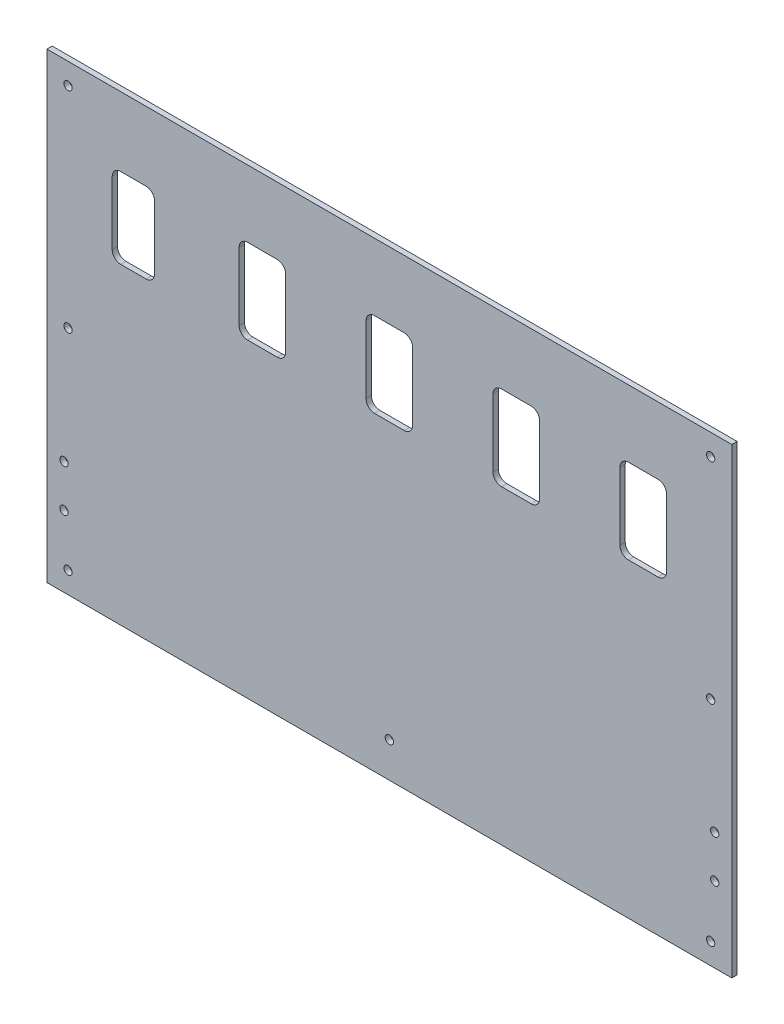
SolidWorks part; units mm, degrees
material "ABS PC"
ref_plane "Front Plane" through (0, 0, 0) normal (0, 0, 1) x (1, 0, 0)
ref_plane "Top Plane" through (0, 0, 0) normal (0, 1, 0) x (1, 0, 0)
ref_plane "Right Plane" through (0, 0, 0) normal (1, 0, 0) x (0, 0, -1)
sketch "Sketch1" plane through (0, 0, 0) normal (0, 0, 1) x (1, 0, 0)
  line L1 (-205.5812, -138.684) -> (205.5812, -138.684)
  line L2 (-205.5812, -138.684) -> (-205.5812, 138.684)
  line L3 (-205.5812, 138.684) -> (205.5812, 138.684)
  line L4 (205.5812, -138.684) -> (205.5812, 138.684)
  line L5 (0, 138.684) -> (0, -138.684) construction
  line L6 (-205.5812, 0) -> (205.5813, 0) construction
  point P0 (0, 0)
  point P4 (-137.0013, 0)
  point P5 (137.0013, 0)
  point P6 (0, 97.0788)
  point P7 (0, -97.0788)
  dimension "Width" = 277.368
  dimension "Break" = 68.58
  dimension "D2" = 68.58
  dimension "D1" = 41.6052
  dimension "D3" = 41.6052
  dimension "D4" = 411.1625
sketch "Sketch2" plane through (0, 0, 0) normal (1, 0, 0) x (0, 0, -1)
  line L0 (-1.5875, -138.684) -> (1.5875, -138.684)
  dimension "Thickness" = 3.175
sketch "Sketch3" plane through (0, 0, 0) normal (0, 0, 1) x (1, 0, 0)
  line L0 (-205.5812, -138.684) -> (-205.5812, 138.684) construction
  line L1 (-205.5812, -138.684) -> (205.5812, -138.684) construction
  line L2 (205.5812, -138.684) -> (205.5812, 138.684) construction
  line L3 (-205.5812, 138.684) -> (205.5812, 138.684) construction
  line L4 (-205.5812, -138.684) -> (-205.5812, 138.684)
  line L5 (-205.5812, -138.684) -> (205.5812, -138.684)
  line L6 (205.5812, -138.684) -> (205.5812, 138.684)
  line L7 (-205.5812, 138.684) -> (205.5812, 138.684)
extrude "Boss-Extrude1" add sketch "Sketch3" along normal mid plane 3.175
sketch "Sketch4" plane through (0, 0, 1.5875) normal (0, 0, 1) x (1, 0, 0)
  line L0 (-227.6475, 73.0327) -> (-161.29, 73.0327) construction
  line L1 (-82.55, 73.0327) -> (-82.55, 98.4327) construction
  line L2 (-82.55, 98.4327) -> (-90.17, 98.4327) construction
  line L3 (-161.29, 73.0327) -> (-161.29, 97.1627) construction
  line L6 (-227.6475, -105.791) -> (-227.6475, 52.959) construction
  line L7 (-227.6475, -115.316) -> (-227.6475, 138.684) construction
  line L8 (-161.29, 73.0327) -> (-82.55, 73.0327) construction
  line L9 (-82.55, 73.0327) -> (-6.35, 73.0327) construction
  line L10 (-6.35, 73.0327) -> (69.85, 73.0327) construction
  line L11 (69.85, 73.0327) -> (146.05, 73.0327) construction
  line L12 (-82.55, 73.0327) -> (-82.55, 47.6327) construction
  line L13 (-82.55, 47.6327) -> (-62.23, 47.6327) construction
  line L16 (-161.29, 97.1627) -> (-166.37, 97.1627) construction
  line L17 (-161.29, 73.0327) -> (-161.29, 48.9027) construction
  line L18 (-161.29, 48.9027) -> (-140.97, 48.9027) construction
  line L19 (-6.35, 73.0327) -> (-6.35, 98.4327) construction
  line L24 (-6.35, 98.4327) -> (-13.97, 98.4327) construction
  line L25 (-6.35, 73.0327) -> (-6.35, 47.6327) construction
  line L26 (-6.35, 47.6327) -> (13.97, 47.6327) construction
  line L27 (69.85, 73.0327) -> (69.85, 98.4327) construction
  line L28 (-8.89, 98.4327) -> (8.89, 98.4327)
  line L29 (-13.97, 93.3527) -> (-13.97, 52.7127)
  line L30 (-8.89, 47.6327) -> (8.89, 47.6327)
  line L31 (13.97, 93.3527) -> (13.97, 52.7127)
  line L32 (69.85, 98.4327) -> (62.23, 98.4327) construction
  line L33 (69.85, 73.0327) -> (69.85, 47.6327) construction
  line L34 (69.85, 47.6327) -> (90.17, 47.6327) construction
  line L35 (146.05, 73.0327) -> (146.05, 98.4327) construction
  line L36 (67.31, 98.4327) -> (85.09, 98.4327)
  line L37 (62.23, 93.3527) -> (62.23, 52.7127)
  line L38 (67.31, 47.6327) -> (85.09, 47.6327)
  line L39 (90.17, 93.3527) -> (90.17, 52.7127)
  line L40 (146.05, 98.4327) -> (138.43, 98.4327) construction
  line L41 (146.05, 73.0327) -> (146.05, 47.6327) construction
  line L42 (146.05, 47.6327) -> (166.37, 47.6327) construction
  line L43 (-205.5812, 138.684) -> (-205.5812, 73.0327) construction
  line L44 (143.51, 98.4327) -> (161.29, 98.4327)
  line L45 (138.43, 93.3527) -> (138.43, 52.7127)
  line L46 (143.51, 47.6327) -> (161.29, 47.6327)
  line L47 (166.37, 93.3527) -> (166.37, 52.7127)
  line L48 (-85.09, 98.4327) -> (-67.31, 98.4327)
  line L49 (-90.17, 93.3527) -> (-90.17, 52.7127)
  line L50 (-85.09, 47.6327) -> (-67.31, 47.6327)
  line L51 (-62.23, 93.3527) -> (-62.23, 52.7127)
  line L53 (-161.29, 97.1627) -> (-146.05, 97.1627)
  line L54 (-166.37, 92.0827) -> (-166.37, 53.9827)
  line L55 (-161.29, 48.9027) -> (-146.05, 48.9027)
  line L56 (-140.97, 92.0827) -> (-140.97, 53.9827)
  arc A0 (138.43, 52.7127) -> (143.51, 47.6327) centre (143.51, 52.7127) ccw
  arc A1 (166.37, 52.7127) -> (161.29, 47.6327) centre (161.29, 52.7127) cw
  arc A2 (161.29, 98.4327) -> (166.37, 93.3527) centre (161.29, 93.3527) cw
  arc A3 (138.43, 93.3527) -> (143.51, 98.4327) centre (143.51, 93.3527) cw
  arc A4 (62.23, 52.7127) -> (67.31, 47.6327) centre (67.31, 52.7127) ccw
  arc A5 (90.17, 52.7127) -> (85.09, 47.6327) centre (85.09, 52.7127) cw
  arc A6 (85.09, 98.4327) -> (90.17, 93.3527) centre (85.09, 93.3527) cw
  arc A7 (67.31, 98.4327) -> (62.23, 93.3527) centre (67.31, 93.3527) ccw
  arc A8 (-13.97, 52.7127) -> (-8.89, 47.6327) centre (-8.89, 52.7127) ccw
  arc A9 (13.97, 52.7127) -> (8.89, 47.6327) centre (8.89, 52.7127) cw
  arc A10 (8.89, 98.4327) -> (13.97, 93.3527) centre (8.89, 93.3527) cw
  arc A11 (-8.89, 98.4327) -> (-13.97, 93.3527) centre (-8.89, 93.3527) ccw
  arc A19 (-90.17, 52.7127) -> (-85.09, 47.6327) centre (-85.09, 52.7127) ccw
  arc A20 (-62.23, 52.7127) -> (-67.31, 47.6327) centre (-67.31, 52.7127) cw
  arc A21 (-67.31, 98.4327) -> (-62.23, 93.3527) centre (-67.31, 93.3527) cw
  arc A22 (-85.09, 98.4327) -> (-90.17, 93.3527) centre (-85.09, 93.3527) ccw
  arc A23 (-166.37, 53.9827) -> (-161.29, 48.9027) centre (-161.29, 53.9827) ccw
  arc A24 (-146.05, 48.9027) -> (-140.97, 53.9827) centre (-146.05, 53.9827) ccw
  arc A25 (-146.05, 97.1627) -> (-140.97, 92.0827) centre (-146.05, 92.0827) cw
  arc A26 (-161.29, 97.1627) -> (-166.37, 92.0827) centre (-161.29, 92.0827) ccw
  point P16 (-76.2, 98.4327)
  point P17 (-90.17, 73.0327)
  point P18 (-13.97, 73.0327)
  point P95 (62.23, 73.0327)
  point P96 (138.43, 73.0327)
  point P97 (0, 98.4327)
  point P98 (76.2, 98.4327)
  point P99 (152.4, 98.4327)
  dimension "D1" = 5.08
  dimension "D2" = 5.08
  dimension "D5" = 5.08
  dimension "D9" = 27.94
  dimension "D10" = 27.94
  dimension "D11" = 27.94
  dimension "D12" = 27.94
  dimension "D3" = 76.2
  dimension "D4" = 76.2
  dimension "D6" = 152.4
  dimension "D7" = 65.6513
extrude "Cut-Extrude1" cut sketch "Sketch4" against normal blind 25.4 contours L53 A26 L54 A23 L55 A24 L56 A25
hole_wizard "#10 Clearance Hole1" positions "Sketch5" profile "Sketch6" hole size "#10" standard "ANSI Inch" end condition through all
sketch "Sketch5" plane through (0, 0, 1.5875) normal (0, 0, 1) x (1, 0, 0)
  line L0 (192.8812, -125.984) -> (192.8812, -138.684) construction
  line L3 (-192.8812, -125.984) -> (-192.8812, -138.684) construction
  line L4 (-205.5812, -138.684) -> (205.5812, -138.684) construction
  line L7 (205.5812, 138.684) -> (-205.5812, 138.684) construction
  line L8 (-192.8812, 138.684) -> (-192.8812, 0) construction
  line L9 (-192.8812, 0) -> (192.8812, 0) construction
  point P6 (192.8812, 125.984)
  point P8 (-192.8812, -125.984)
  point P10 (192.8812, -125.984)
  point P12 (-192.8812, 125.984)
  point P27 (-192.8812, 0)
  point P29 (192.8812, 0)
  point P37 (-192.8812, 125.984)
  point P39 (192.8812, 125.984)
  dimension "D1" = 12.7
  dimension "D2" = 12.7
  dimension "D3" = 12.7
  dimension "D4" = 12.7
sketch "Sketch6" plane through (192.8812, 125.984, 1.5875) normal (1, 0, 0) x (0, -1, 0)
  line L0 (0, 0) -> (0, 3.175)
  line L1 (0, 3.175) -> (2.4892, 3.175)
  line L2 (2.4892, 3.175) -> (2.4892, 0)
  line L5 (2.4892, 0) -> (0, 0)
  line L11 (0, -6.35) -> (0, 107.95) construction
  dimension "Thru Hole Dia." = 4.9784
  dimension "Thru Hole Depth" = 3.175
hole_wizard "#10 Clearance Hole2" positions "Sketch7" profile "Sketch8" hole size "#10" standard "ANSI Inch" end condition through all
sketch "Sketch7" plane through (0, 0, 1.5875) normal (0, 0, 1) x (1, 0, 0)
  point P0 (0, -117.5325)
sketch "Sketch8" plane through (0, -117.5325, 1.5875) normal (1, 0, 0) x (0, -1, 0)
  line L0 (0, 0) -> (0, 3.175)
  line L1 (0, 3.175) -> (2.4892, 3.175)
  line L2 (2.4892, 3.175) -> (2.4892, 0)
  line L5 (2.4892, 0) -> (0, 0)
  line L11 (0, -6.35) -> (0, 107.95) construction
  dimension "Thru Hole Dia." = 4.9784
  dimension "Thru Hole Depth" = 3.175
hole_wizard "#10 Clearance Hole3" positions "Sketch9" profile "Sketch10" hole size "#10" standard "ANSI Inch" end condition through all
sketch "Sketch9" plane through (0, 0, 1.5875) normal (0, 0, 1) x (1, 0, 0)
  point P0 (-195.3063, -70.6157)
sketch "Sketch10" plane through (-195.3063, -70.6157, 1.5875) normal (1, 0, 0) x (0, -1, 0)
  line L0 (0, 0) -> (0, 3.175)
  line L1 (0, 3.175) -> (2.4892, 3.175)
  line L2 (2.4892, 3.175) -> (2.4892, 0)
  line L5 (2.4892, 0) -> (0, 0)
  line L11 (0, -6.35) -> (0, 107.95) construction
  dimension "Thru Hole Dia." = 4.9784
  dimension "Thru Hole Depth" = 3.175
hole_wizard "#10 Clearance Hole4" positions "Sketch11" profile "Sketch12" hole size "#10" standard "ANSI Inch" end condition through all
sketch "Sketch11" plane through (0, 0, 1.5875) normal (0, 0, 1) x (1, 0, 0)
  point P1 (-195.3063, -96.0157)
  point P3 (-195.3063, -96.0157)
sketch "Sketch12" plane through (-195.3063, -96.0157, 1.5875) normal (1, 0, 0) x (0, -1, 0)
  line L0 (0, 0) -> (0, 3.175)
  line L1 (0, 3.175) -> (2.4892, 3.175)
  line L2 (2.4892, 3.175) -> (2.4892, 0)
  line L5 (2.4892, 0) -> (0, 0)
  line L11 (0, -6.35) -> (0, 107.95) construction
  dimension "Thru Hole Dia." = 4.9784
  dimension "Thru Hole Depth" = 3.175
hole_wizard "#10 Clearance Hole5" positions "Sketch13" profile "Sketch14" hole size "#10" standard "ANSI Inch" end condition through all
sketch "Sketch13" plane through (0, 0, 1.5875) normal (0, 0, 1) x (1, 0, 0)
  point P0 (195.3062, -68.0242)
  point P2 (195.3062, -93.4242)
sketch "Sketch14" plane through (195.3062, -68.0242, 1.5875) normal (1, 0, 0) x (0, -1, 0)
  line L0 (0, 0) -> (0, 3.175)
  line L1 (0, 3.175) -> (2.4892, 3.175)
  line L2 (2.4892, 3.175) -> (2.4892, 0)
  line L5 (2.4892, 0) -> (0, 0)
  line L11 (0, -6.35) -> (0, 107.95) construction
  dimension "Thru Hole Dia." = 4.9784
  dimension "Thru Hole Depth" = 3.175
equation "\"D1@Boss-Extrude1\" = \"Thickness@Sketch2\""
equation "\"D2@Sketch1\" = \"Break@Sketch1\""
equation "\"D1@Sketch1\"=\"Width@Sketch1\"*0.15"
equation "\"D3@Sketch1\"=\"D1@Sketch1\""
equation "\"SlotWidth\"= 1.1in"
equation "\"D9@Sketch4\"=\"SlotWidth\""
equation "\"D10@Sketch4\"=\"SlotWidth\""
equation "\"D11@Sketch4\"=\"SlotWidth\""
equation "\"D12@Sketch4\"=\"SlotWidth\""
